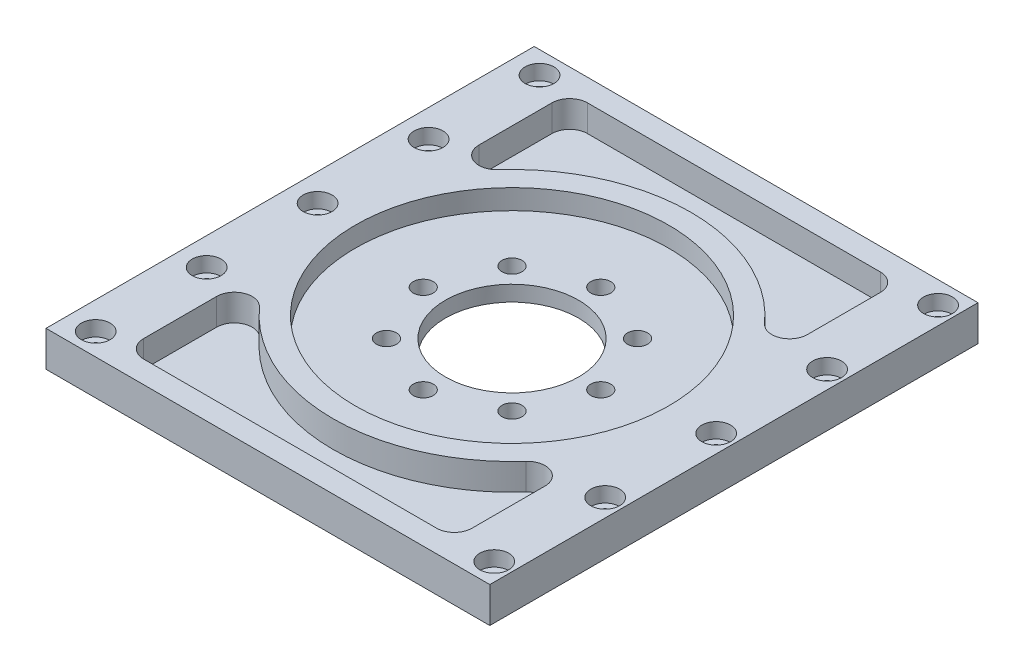
SolidWorks part; units mm, degrees
material "6061-T6 (SS)"
ref_plane "Front Plane" through (0, 0, 0) normal (0, 0, 1) x (1, 0, 0)
ref_plane "Top Plane" through (0, 0, 0) normal (0, 1, 0) x (1, 0, 0)
ref_plane "Right Plane" through (0, 0, 0) normal (1, 0, 0) x (0, 0, -1)
sketch "Sketch1" plane through (0, 0, 0) normal (0, 1, 0) x (1, 0, 0)
  line L1 (0, 0) -> (100, 0)
  line L2 (0, 0) -> (0, 110)
  line L3 (0, 110) -> (100, 110)
  line L4 (100, 0) -> (100, 110)
  dimension "D1" = 110
  dimension "D2" = 100
extrude "Boss-Extrude1" add sketch "Sketch1" along normal blind 8
sketch "Sketch2" plane through (0, 8, 0) normal (0, 1, 0) x (1, 0, 0)
  line L0 (0, 110) -> (6.2, 110)
  line L1 (100, 110) -> (0, 110) construction
  line L2 (6.2, 110) -> (6.2, 0)
  line L3 (0, 0) -> (100, 0) construction
  line L4 (0, 110) -> (0, 0) construction
  line L5 (96, 110) -> (96, 0) construction
  line L7 (100, 0) -> (100, 110) construction
  line L8 (0, 55) -> (6.2, 55) construction
  point P11 (6.2, 105)
  point P18 (6.2, 80)
  point P19 (6.2, 55)
  point P20 (6.2, 30)
  point P21 (6.2, 5)
  point P32 (96, 55)
  point P41 (96, 30)
  point P42 (96, 5)
  point P43 (96, 55)
  point P44 (96, 30)
  point P45 (96, 80)
  point P46 (96, 55)
  point P47 (96, 80)
  point P48 (96, 105)
  dimension "D1" = 5
  dimension "D3" = 6.2
  dimension "D4" = 4
  dimension "D5" = 3
  dimension "D6" = 3
hole_wizard "CBORE for M3 Hex Socket Head Cap Screw1" positions "Sketch2" profile "Sketch3" counterbore size "M3" standard "DIN"
sketch "Sketch3" plane through (96, 8, -105) normal (1, 0, 0) x (0, 0, 1)
  line L0 (0, 0) -> (0, 9.0215)
  line L1 (0, 9.0215) -> (1.7, 8)
  line L2 (1.7, 8) -> (1.7, 3.4)
  line L3 (1.7, 3.4) -> (3.25, 3.4)
  line L4 (3.25, 3.4) -> (3.25, 0)
  line L5 (3.25, 0) -> (0, 0)
  line L10 (0, 9.0215) -> (-1.7, 8) construction
  line L11 (0, -6.35) -> (0, 107.95) construction
  dimension "Hole Dia." = 3.4
  dimension "Hole Depth" = 8
  dimension "C'Bore Dia." = 6.5
  dimension "C'Bore Depth" = 3.4
  dimension "Drill Angle" = 118
sketch "Sketch6" plane through (0, 8, 0) normal (0, 1, 0) x (1, 0, 0)
  line L2 (100, 110) -> (0, 110) construction
  line L3 (100, 110) -> (0, 0)
  line L4 (0, 0) -> (0, 110)
  line L5 (0, 110) -> (100, 0)
  line L6 (0, 0) -> (100, 0) construction
  point P19 (50, 55)
hole_wizard "Ø30.0 (30) Diameter Hole1" positions "Sketch6" profile "Sketch5" hole size "Ø30.0" standard "DIN"
sketch "Sketch5" plane through (50, 8, -55) normal (1, 0, 0) x (0, 0, 1)
  line L0 (0, 0) -> (0, 19.0129)
  line L1 (0, 19.0129) -> (15, 10)
  line L2 (15, 10) -> (15, 0)
  line L5 (15, 0) -> (0, 0)
  line L10 (0, 19.0129) -> (-15, 10) construction
  line L11 (0, -6.35) -> (0, 107.95) construction
  dimension "Hole Dia." = 30
  dimension "Hole Depth" = 10
  dimension "Drill Angle" = 118
sketch "Sketch7" plane through (0, 8, 0) normal (0, 1, 0) x (1, 0, 0)
  circle A0 centre (50, 55) radius 35.3
  dimension "D1" = 70.6
extrude "Cut-Extrude1" cut sketch "Sketch7" against normal blind 4.5
sketch "Sketch10" plane through (0, 0, 0) normal (0, -1, 0) x (-1, 0, 0)
  circle A0 centre (-50, 55) radius 20
  point P5 (-50, 75)
  point P13 (-35.8579, 69.1421)
  point P14 (-30, 55)
  point P15 (-35.8579, 40.8579)
  point P16 (-50, 35)
  point P17 (-64.1421, 40.8579)
  point P18 (-70, 55)
  point P19 (-64.1421, 69.1421)
  dimension "D1" = 40
  dimension "D2" = 8
hole_wizard "M4 Clearance Hole1" positions "Sketch10" profile "Sketch11" hole size "M4" standard "DIN" end condition through all
sketch "Sketch11" plane through (64.1421, 0, -69.1421) normal (1, 0, 0) x (0, 0, -1)
  line L0 (0, 0) -> (0, 8)
  line L1 (0, 8) -> (2.25, 8)
  line L2 (2.25, 8) -> (2.25, 0)
  line L5 (2.25, 0) -> (0, 0)
  line L11 (0, -6.35) -> (0, 107.95) construction
  dimension "Thru Hole Dia." = 4.5
  dimension "Thru Hole Depth" = 8
sketch "Sketch12" plane through (0, 8, 0) normal (0, 1, 0) x (1, 0, 0)
  line L4 (13, 110) -> (13, 0)
  line L5 (100, 110) -> (0, 110) construction
  line L6 (0, 0) -> (100, 0) construction
  line L7 (87, 105) -> (87, 5)
  line L8 (5, 105) -> (5, 5)
  line L9 (5, 5) -> (95, 5)
  line L10 (95, 5) -> (95, 105)
  line L11 (95, 105) -> (5, 105)
  line L12 (5, 105) -> (5, 5)
  line L13 (5, 5) -> (95, 5)
  line L14 (95, 5) -> (95, 105)
  line L15 (95, 105) -> (5, 105)
  circle A2 centre (50, 55) radius 40.3
  circle A3 centre (50, 55) radius 40.3
  dimension "D3" = 8
  dimension "D4" = 8
  dimension "D1" = 5
  dimension "D2" = 5
extrude "Cut-Extrude2" cut sketch "Sketch12" against normal blind 6 contours A3 L7 L15 L4 | A3 L4 L13 L7
fillet "Fillet1" radius 4 8 edges at (13, 5, -39.0285) (87, 5, -5) (87, 5, -39.0285) (13, 5, -5) (87, 5, -70.9715) (13, 5, -105) (13, 5, -70.9715) (87, 5, -105)
